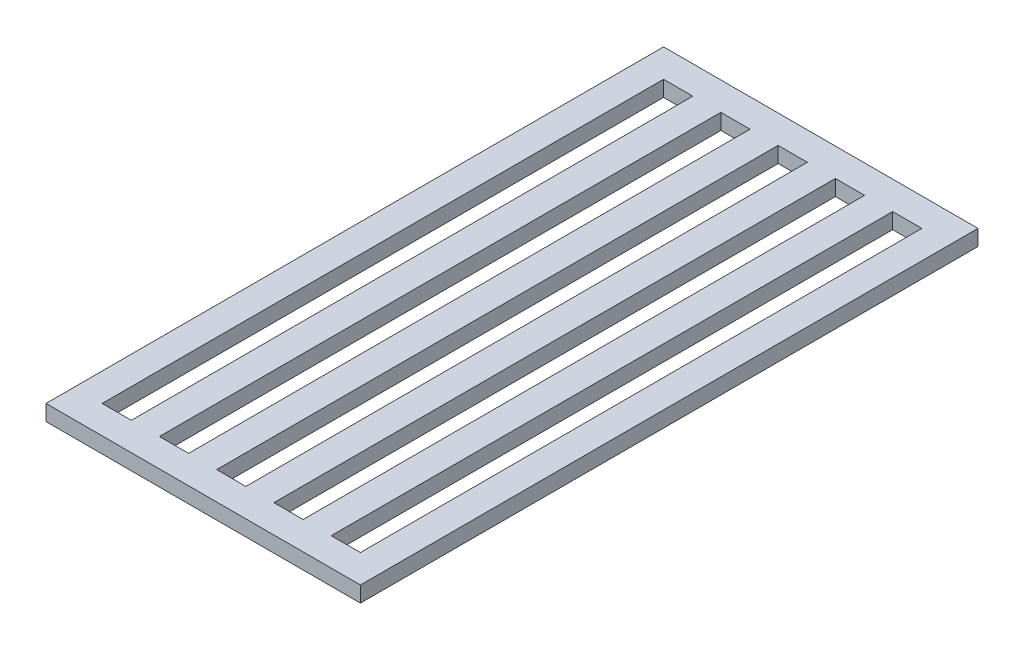
SolidWorks part; units mm, degrees
ref_plane "Front Plane" through (0, 0, 0) normal (0, 0, 1) x (1, 0, 0)
ref_plane "Top Plane" through (0, 0, 0) normal (0, 1, 0) x (1, 0, 0)
ref_plane "Right Plane" through (0, 0, 0) normal (1, 0, 0) x (0, 0, -1)
sketch "Sketch1" plane through (0, 0, 0) normal (0, 1, 0) x (1, 0, 0)
  line L0 (15.2, 5) -> (15.2, 105)
  line L1 (0, 0) -> (56, 0)
  line L2 (0, 0) -> (0, 110)
  line L3 (0, 110) -> (56, 110)
  line L4 (56, 0) -> (56, 110)
  line L5 (5, 5) -> (10.2, 5)
  line L6 (5, 5) -> (5, 105)
  line L7 (5, 105) -> (10.2, 105)
  line L8 (10.2, 5) -> (10.2, 105)
  line L9 (15.2, 5) -> (20.4, 5)
  line L10 (20.4, 5) -> (20.4, 105)
  line L11 (15.2, 105) -> (20.4, 105)
  line L12 (25.4, 5) -> (25.4, 105)
  line L13 (25.4, 5) -> (30.6, 5)
  line L14 (30.6, 5) -> (30.6, 105)
  line L15 (25.4, 105) -> (30.6, 105)
  line L16 (35.6, 5) -> (35.6, 105)
  line L17 (35.6, 5) -> (40.8, 5)
  line L18 (40.8, 5) -> (40.8, 105)
  line L19 (35.6, 105) -> (40.8, 105)
  line L20 (45.8, 5) -> (45.8, 105)
  line L21 (45.8, 5) -> (51, 5)
  line L22 (51, 5) -> (51, 105)
  line L23 (45.8, 105) -> (51, 105)
  line L64 (5, 42) -> (5, 142) [skipped]
  line L65 (5, 142) -> (10.2, 142) [skipped]
  line L66 (10.2, 42) -> (10.2, 142) [skipped]
  line L67 (5, 42) -> (10.2, 42) [skipped]
  line L68 (15.2, 42) -> (15.2, 142) [skipped]
  line L69 (15.2, 142) -> (20.4, 142) [skipped]
  line L70 (20.4, 42) -> (20.4, 142) [skipped]
  line L71 (15.2, 42) -> (20.4, 42) [skipped]
  line L72 (25.4, 42) -> (25.4, 142) [skipped]
  line L73 (25.4, 142) -> (30.6, 142) [skipped]
  line L74 (30.6, 42) -> (30.6, 142) [skipped]
  line L75 (25.4, 42) -> (30.6, 42) [skipped]
  line L76 (35.6, 42) -> (35.6, 142) [skipped]
  line L77 (35.6, 142) -> (40.8, 142) [skipped]
  line L78 (40.8, 42) -> (40.8, 142) [skipped]
  line L79 (35.6, 42) -> (40.8, 42) [skipped]
  line L80 (45.8, 42) -> (45.8, 142) [skipped]
  line L81 (45.8, 142) -> (51, 142) [skipped]
  line L82 (51, 42) -> (51, 142) [skipped]
  line L83 (45.8, 79) -> (45.8, 179) [skipped]
  line L84 (45.8, 179) -> (51, 179) [skipped]
  line L85 (51, 79) -> (51, 179) [skipped]
  line L86 (45.8, 79) -> (51, 79) [skipped]
  line L87 (35.6, 79) -> (35.6, 179) [skipped]
  line L88 (35.6, 179) -> (40.8, 179) [skipped]
  line L89 (40.8, 79) -> (40.8, 179) [skipped]
  line L90 (35.6, 79) -> (40.8, 79) [skipped]
  line L91 (25.4, 79) -> (25.4, 179) [skipped]
  line L92 (25.4, 179) -> (30.6, 179) [skipped]
  line L93 (30.6, 79) -> (30.6, 179) [skipped]
  line L94 (25.4, 79) -> (30.6, 79) [skipped]
  line L95 (15.2, 79) -> (15.2, 179) [skipped]
  line L96 (15.2, 179) -> (20.4, 179) [skipped]
  line L97 (20.4, 79) -> (20.4, 179) [skipped]
  line L98 (15.2, 79) -> (20.4, 79) [skipped]
  line L99 (5, 79) -> (5, 179) [skipped]
  line L100 (10.2, 79) -> (10.2, 179) [skipped]
  line L101 (5, 79) -> (10.2, 79) [skipped]
  line L102 (45.8, 42) -> (51, 42) [skipped]
  line L103 (5, 179) -> (10.2, 179) [skipped]
  dimension "D1" = 5.2
  dimension "D2" = 5
  dimension "D3" = 100
  dimension "D4" = 5
  dimension "D5" = 5
  dimension "D8" = 5
  dimension "D9" = 5
  dimension "D6" = 5
  dimension "D7" = 3
extrude "Boss-Extrude1" add sketch "Sketch1" along normal blind 2.8
